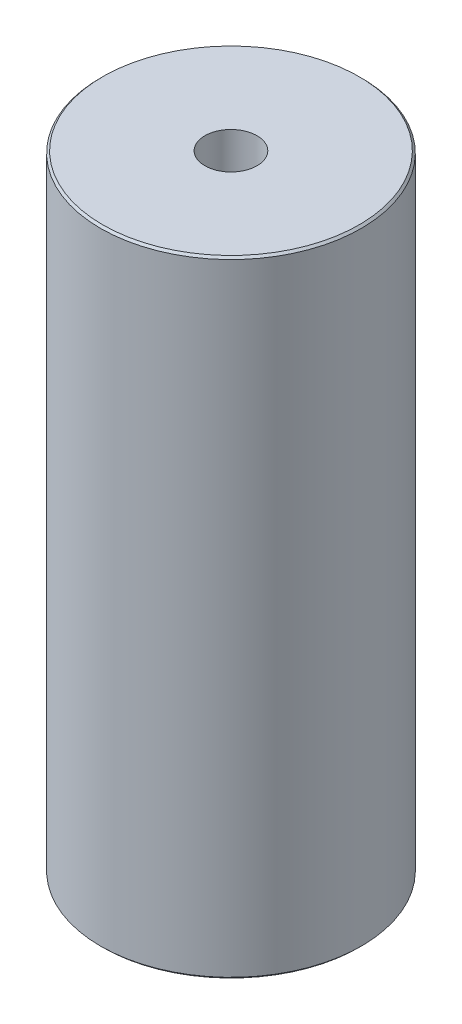
SolidWorks part; units mm, degrees
material "电木板A级"
ref_plane "前视" through (0, 0, 0) normal (0, 0, 1) x (1, 0, 0)
ref_plane "上视" through (0, 0, 0) normal (0, 1, 0) x (1, 0, 0)
ref_plane "右视" through (0, 0, 0) normal (1, 0, 0) x (0, 0, -1)
sketch "草图1" plane through (0, 0, 0) normal (0, 1, 0) x (1, 0, 0)
  circle A0 centre (0, 0) radius 12.5
  dimension "D1" = 25
extrude "凸台-拉伸1" add sketch "草图1" along normal blind 60
hole_wizard "M6 螺纹孔1" positions "草图3" profile "草图2" tap size "M6" standard "Gb"
sketch "草图3" plane through (0, 60, 0) normal (0, 1, 0) x (1, 0, 0)
  point P0 (0, 0)
sketch "草图2" plane through (0, 60, 0) normal (1, 0, 0) x (0, 0, 1)
  line L0 (0, 0) -> (0, 16.5022)
  line L1 (0, 16.5022) -> (2.5, 15)
  line L2 (2.5, 15) -> (2.5, 0)
  line L5 (2.5, 0) -> (0, 0)
  line L10 (0, 16.5022) -> (-2.5, 15) construction
  line L11 (0, -6.35) -> (0, 107.95) construction
  dimension "螺纹孔钻头直径" = 5
  dimension "螺纹孔钻头深度" = 15
  dimension "导头角度" = 118
cosmetic thread "孔螺蚊线1" parameters "D1"=12, "D2"=6
chamfer "倒角1" distance 0.2 angle 45 2 edges at (0, 0, 12.5) (0, 60, 12.5)
